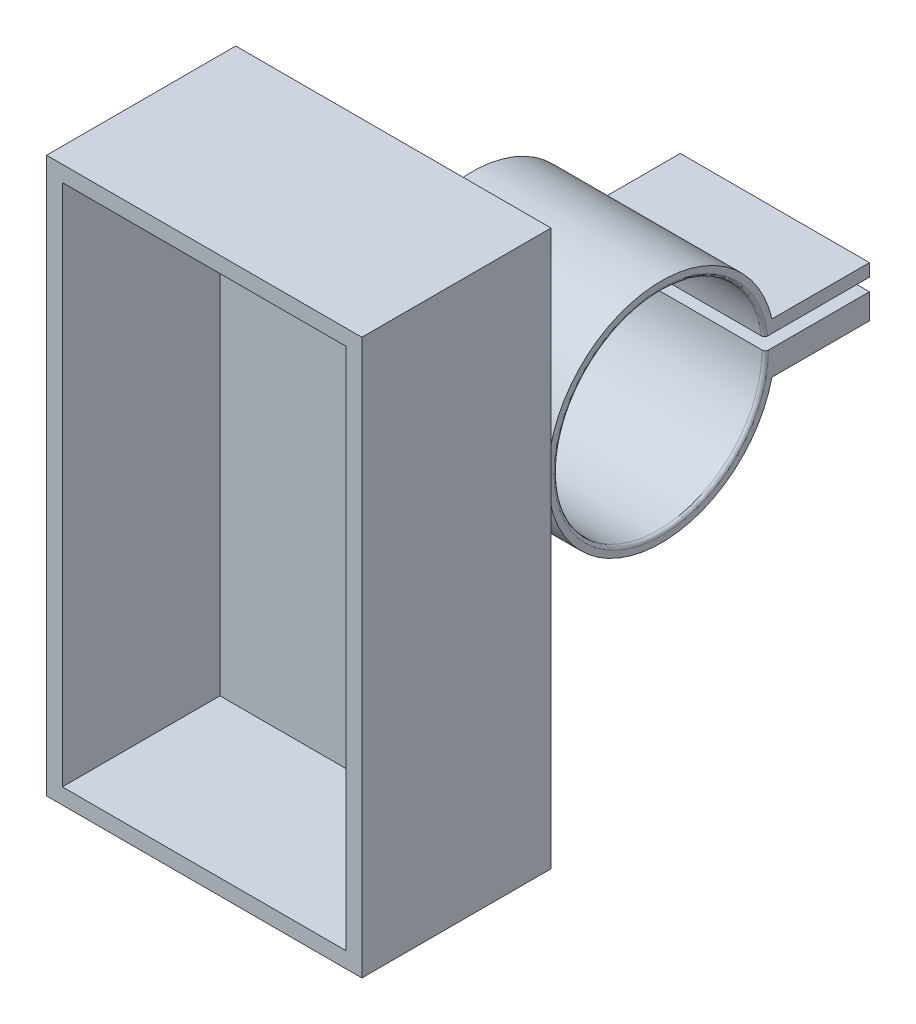
SolidWorks part; units mm, degrees
ref_plane "Plano frontal" through (0, 0, 0) normal (0, 0, 1) x (1, 0, 0)
ref_plane "Plano superior" through (0, 0, 0) normal (0, 1, 0) x (1, 0, 0)
ref_plane "Plano direito" through (0, 0, 0) normal (1, 0, 0) x (0, 0, -1)
sketch "Esboço1" plane through (0, 0, 0) normal (0, 0, 1) x (1, 0, 0)
  line L1 (25, -44) -> (-25, -44)
  line L2 (25, -44) -> (25, 44)
  line L3 (25, 44) -> (-25, 44)
  line L4 (-25, -44) -> (-25, 44)
  line L5 (25, -44) -> (-25, 44) construction
  line L6 (25, 44) -> (-25, -44) construction
  point P0 (0, 0)
  dimension "D1" = 50
  dimension "D2" = 88
extrude "Ressalto-extrusão1" add sketch "Esboço1" along normal blind 30
sketch "Esboço3" plane through (0, 0, 30) normal (0, 0, 1) x (1, 0, 0)
  line L1 (22.5, -41.5) -> (-22.5, -41.5)
  line L2 (22.5, -41.5) -> (22.5, 41.5)
  line L3 (22.5, 41.5) -> (-22.5, 41.5)
  line L4 (-22.5, -41.5) -> (-22.5, 41.5)
  line L5 (22.5, -41.5) -> (-22.5, 41.5) construction
  line L6 (22.5, 41.5) -> (-22.5, -41.5) construction
  point P0 (0, 0)
  dimension "D1" = 45
  dimension "D2" = 83
extrude "Corte-extrusão1" cut sketch "Esboço3" against normal blind 25
sketch "Esboço7" plane through (0, 0, 0) normal (0, 0, -1) x (-1, 0, 0)
  circle A0 centre (0, 0) radius 10.25
  dimension "D1" = 20.5
extrude "Ressalto-extrusão3" add sketch "Esboço7" along normal blind 15
fillet "Filete1" radius 4 1 edges at (-10.25, 0, 0)
sketch "Esboço9" plane through (0, 0, 0) normal (1, 0, 0) x (0, 0, -1)
  circle A0 centre (27.4794, 0) radius 18
  dimension "D1" = 36
extrude "Ressalto-extrusão4" add sketch "Esboço9" along normal blind 15 and the other way blind 15
sketch "Esboço10" plane through (15, 0, 0) normal (1, 0, 0) x (0, 0, -1)
  circle A0 centre (27.4794, 0) radius 16.5
  point P0 (27.4794, 0)
  dimension "D1" = 33
extrude "Corte-extrusão2" cut sketch "Esboço10" against normal blind 40
sketch "Esboço11" plane through (0, 0, 0) normal (1, 0, 0) x (0, 0, -1)
  line L1 (60.4926, 0) -> (60.4926, 4)
  line L2 (60.4926, 4) -> (45.0293, 4)
  line L3 (60.4926, 0) -> (60.4926, -4)
  line L4 (60.4926, -4) -> (45.0293, -4)
  line L5 (45.0293, 4) -> (45.0293, -4)
  circle A0 centre (27.4794, 0) radius 18 construction
  dimension "D1" = 15.4633
  dimension "D2" = 4
  dimension "D3" = 4
  dimension "D4" = 8
extrude "Ressalto-extrusão5" add sketch "Esboço11" along normal blind 15 and the other way blind 15
sketch "Esboço12" plane through (15, 0, 0) normal (1, 0, 0) x (0, 0, -1)
  line L1 (60.4926, -4) -> (60.4926, 4) construction
  line L2 (60.4926, 0) -> (60.4926, 2)
  line L4 (60.4926, 2) -> (43.4926, 2)
  line L5 (43.4926, 2) -> (43.4926, 0)
  line L7 (43.4926, 0) -> (60.4926, 0)
  dimension "D1" = 17
  dimension "D2" = 2
  dimension "D3" = 2
extrude "Corte-extrusão3" cut sketch "Esboço12" against normal blind 40
fillet "Filete2" radius 0.5 1 edges at (15, -1.0018, -11.0098)
fillet "Filete3" radius 0.5 1 edges at (-15, -1.0018, -11.0098)
